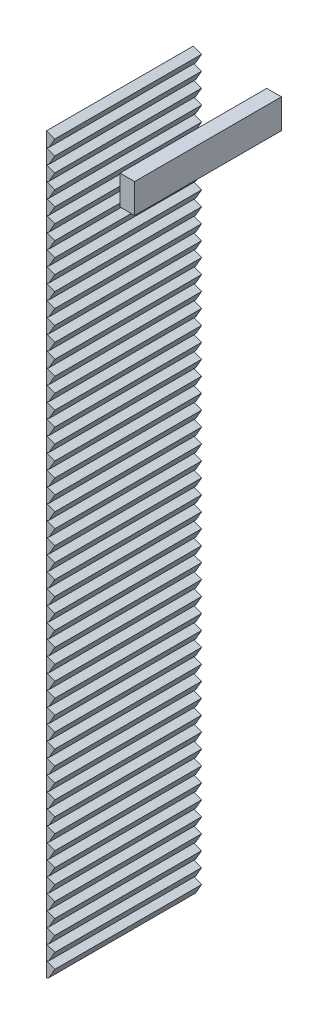
SolidWorks part; units mm, degrees
ref_plane "前基準面" through (0, 0, 0) normal (0, 0, 1) x (1, 0, 0)
ref_plane "上基準面" through (0, 0, 0) normal (0, 1, 0) x (1, 0, 0)
ref_plane "右基準面" through (0, 0, 0) normal (1, 0, 0) x (0, 0, -1)
sketch "草圖2" plane through (0, 0, 0) normal (0, 0, 1) x (1, 0, 0)
  line L1 (50, 500) -> (60, 500)
  line L2 (50, 500) -> (50, 480)
  line L3 (50, 480) -> (60, 480)
  line L4 (60, 500) -> (60, 480)
  dimension "D1" = 20
  dimension "D2" = 10
  dimension "D3" = 50
  dimension "D4" = 480
extrude "填料-伸長2" add sketch "草圖2" along normal blind 100 separate body
sketch "草圖1" plane through (0, 0, 0) normal (0, 0, 1) x (1, 0, 0)
  line L0 (0, 0) -> (0, 10)
  line L1 (0, 10) -> (5.6382, 7.9479)
  line L2 (5.6382, 7.9479) -> (1.5742, 0.9088)
  line L3 (1.5742, 0.9088) -> (0, 0)
  dimension "D1" = 10
  dimension "D2" = 6
  dimension "D3" = 60
  dimension "D4" = 70
  dimension "D5" = 80
extrude "填料-伸長1" add sketch "草圖1" along normal blind 100
pattern_linear "直線複製排列1" count 50 spacing 10 along (0, 1, 0) of "填料-伸長1"
